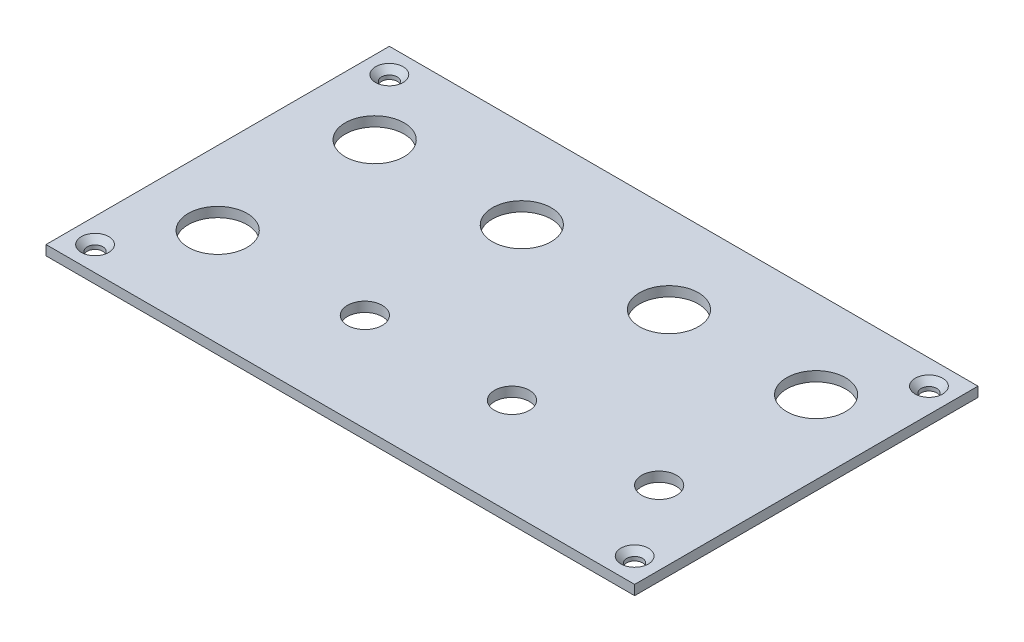
SolidWorks part; units mm, degrees
ref_plane "Front Plane" through (0, 0, 0) normal (0, 0, 1) x (1, 0, 0)
ref_plane "Top Plane" through (0, 0, 0) normal (0, 1, 0) x (1, 0, 0)
ref_plane "Right Plane" through (0, 0, 0) normal (1, 0, 0) x (0, 0, -1)
sketch "Bottom Plate" plane through (0, 0, 0) normal (0, 1, 0) x (1, 0, 0)
  line L1 (0, 0) -> (-120, 0)
  line L2 (0, 0) -> (0, 70)
  line L3 (0, 70) -> (-120, 70)
  line L4 (-120, 0) -> (-120, 70)
  dimension "D1" = 120
  dimension "D2" = 70
extrude "Bottom Plate EXT" add sketch "Bottom Plate" along normal blind 2
sketch "Top Row" plane through (0, 2, 0) normal (0, 1, 0) x (1, 0, 0)
  line L0 (-120, 70) -> (-120, 0) construction
  line L1 (0, 70) -> (-120, 70) construction
  circle A0 centre (-105, 52) radius 6
  circle A1 centre (-75, 52) radius 6
  circle A2 centre (-45, 52) radius 6
  circle A3 centre (-15, 52) radius 6
  dimension "D1" = 12
  dimension "D2" = 30
  dimension "D6" = 30
  dimension "D3" = 30
  dimension "D4" = 15
  dimension "D5" = 18
extrude "Top Row Cut" cut sketch "Top Row" against normal through all
sketch "Bottom Row" plane through (0, 2, 0) normal (0, 1, 0) x (1, 0, 0)
  line L1 (-120, 70) -> (-120, 0) construction
  circle A0 centre (-75, 20) radius 3.55
  circle A1 centre (-45, 20) radius 3.55
  circle A2 centre (-15, 20) radius 3.55
  circle A5 centre (-105, 20) radius 6
  circle A6 centre (-105, 52) radius 6 construction
  dimension "D1" = 7.1
  dimension "D2" = 32
  dimension "D3" = 30
  dimension "D4" = 30
  dimension "D5" = 30
  dimension "D6" = 15
extrude "Bottom Row Cut" cut sketch "Bottom Row" against normal through all
sketch "Plate Screws" plane through (0, 2, 0) normal (0, 1, 0) x (1, 0, 0)
  line L0 (0, 70) -> (-120, 70) construction
  line L1 (-120, 70) -> (-120, 0) construction
  line L2 (-120, 0) -> (0, 0) construction
  line L3 (0, 0) -> (0, 70) construction
  circle A0 centre (-115, 65) radius 1.6
  circle A1 centre (-5, 65) radius 1.6
  circle A2 centre (-5, 5) radius 1.6
  circle A3 centre (-115, 5) radius 1.6
  dimension "D1" = 3.2
  dimension "D2" = 5
  dimension "D3" = 5
  dimension "D4" = 5
  dimension "D5" = 5
extrude "Plate Screws Cut" cut sketch "Plate Screws" against normal through all
sketch "Plate Screw Head" plane through (0, 2, 0) normal (0, 1, 0) x (1, 0, 0)
  circle A0 centre (-115, 65) radius 2.8
  circle A1 centre (-5, 65) radius 2.8
  circle A2 centre (-5, 5) radius 2.8
  circle A3 centre (-115, 5) radius 2.8
  dimension "D1" = 5.6
extrude "Plate Screw Head Cut" cut sketch "Plate Screw Head" against normal blind 2 draft 45
